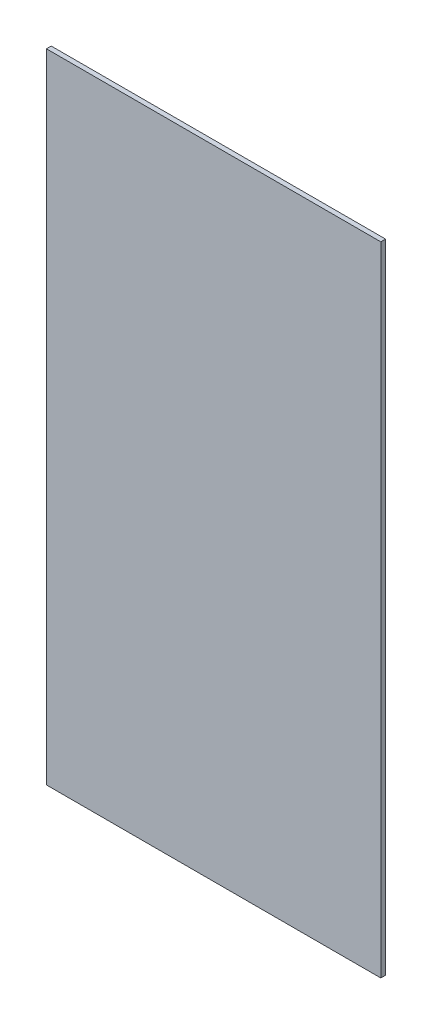
SolidWorks part; units mm, degrees
ref_plane "Спереди" through (0, 0, 0) normal (0, 0, 1) x (1, 0, 0)
ref_plane "Сверху" through (0, 0, 0) normal (0, 1, 0) x (1, 0, 0)
ref_plane "Справа" through (0, 0, 0) normal (1, 0, 0) x (0, 0, -1)
sketch "Эскиз1" plane through (0, 0, 0) normal (0, 1, 0) x (1, 0, 0)
  line L1 (-144.7882, -2.3414) -> (134.7883, -2.3414)
  line L2 (-144.7882, -2.3414) -> (-144.7882, -6.3414)
  line L3 (-144.7882, -6.3414) -> (134.7883, -6.3414)
  line L4 (134.7883, -2.3414) -> (134.7883, -6.3414)
extrude "Вытянуть1" add sketch "Эскиз1" along normal blind 533
